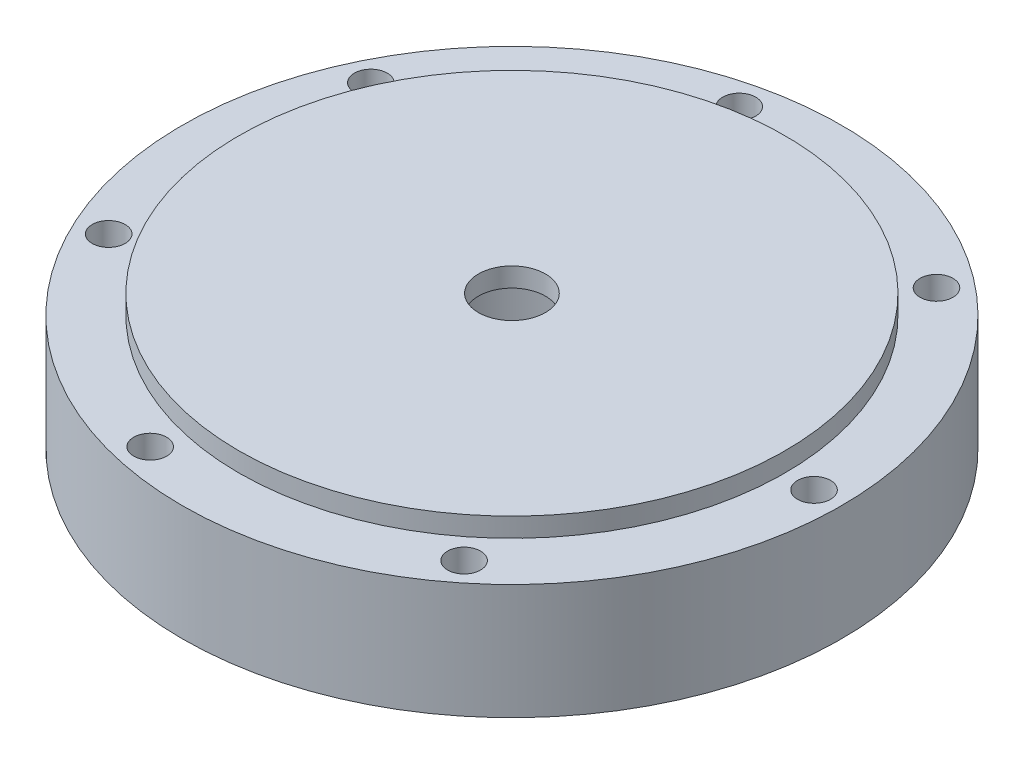
SolidWorks part; units mm, degrees
ref_plane "Alzado" through (0, 0, 0) normal (0, 0, 1) x (1, 0, 0)
ref_plane "Planta" through (0, 0, 0) normal (0, 1, 0) x (1, 0, 0)
ref_plane "Vista lateral" through (0, 0, 0) normal (1, 0, 0) x (0, 0, -1)
sketch "Croquis1" plane through (0, 0, 0) normal (0, 1, 0) x (1, 0, 0)
  circle A0 centre (0, 0) radius 24.85
  circle A1 centre (0, 0) radius 3.05
  dimension "D1" = 49.7
  dimension "D2" = 6.1
extrude "Saliente-Extruir1" add sketch "Croquis1" along normal blind 1.75
sketch "Croquis2" plane through (0, 0, 0) normal (0, 1, 0) x (1, 0, 0)
  line L0 (-4.1352, 9.05) -> (4.1352, 9.05)
  line L1 (-4.1352, -9.05) -> (4.1352, -9.05)
  circle A0 centre (0, 0) radius 30
  arc A1 (-4.5921, 8.9395) -> (-4.5921, -8.9395) centre (0, 0) ccw
  arc A2 (4.5921, -8.9395) -> (4.5921, 8.9395) centre (0, 0) ccw
  arc A3 (4.1352, -9.05) -> (4.5921, -8.9395) centre (4.1352, -8.05) ccw
  arc A4 (-4.1352, -9.05) -> (-4.5921, -8.9395) centre (-4.1352, -8.05) cw
  arc A5 (4.1352, 9.05) -> (4.5921, 8.9395) centre (4.1352, 8.05) cw
  arc A6 (-4.1352, 9.05) -> (-4.5921, 8.9395) centre (-4.1352, 8.05) ccw
  point P9 (4.3704, -9.05)
  dimension "D1" = 60
  dimension "D2" = 20.1
  dimension "D5" = 1
  dimension "D3" = 18.1
  dimension "D4" = 9.05
extrude "Saliente-Extruir2" add sketch "Croquis2" against normal blind 10.5
sketch "Croquis3" plane through (0, 0, 0) normal (0, 1, 0) x (1, 0, 0)
  circle A0 centre (27.5, 0) radius 1.5
  circle A1 centre (17.146, -21.5004) radius 1.5
  circle A2 centre (-6.1193, -26.8105) radius 1.5
  circle A3 centre (-24.7766, -11.9318) radius 1.5
  circle A4 centre (-24.7766, 11.9318) radius 1.5
  circle A5 centre (-6.1193, 26.8105) radius 1.5
  circle A6 centre (17.146, 21.5004) radius 1.5
  point P17 (0, 0)
  dimension "D2" = 3
  dimension "D1" = 27.5
  dimension "D3" = 7
extrude "Cortar-Extruir1" cut sketch "Croquis3" against normal through all
